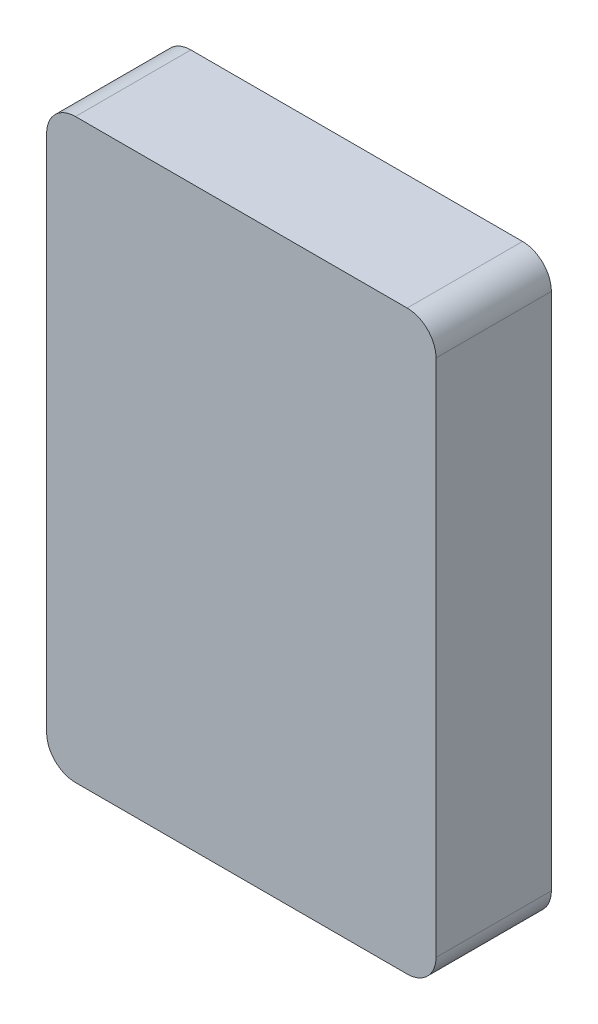
SolidWorks part; units mm, degrees
ref_plane "Front Plane" through (0, 0, 0) normal (0, 0, 1) x (1, 0, 0)
ref_plane "Top Plane" through (0, 0, 0) normal (0, 1, 0) x (1, 0, 0)
ref_plane "Right Plane" through (0, 0, 0) normal (1, 0, 0) x (0, 0, -1)
sketch "Sketch1" plane through (0, 0, 0) normal (0, 0, 1) x (1, 0, 0)
  line L1 (-13.5, 20) -> (13.5, 20)
  line L2 (-13.5, 20) -> (-13.5, -20)
  line L3 (-13.5, -20) -> (13.5, -20)
  line L4 (13.5, 20) -> (13.5, -20)
  line L5 (-13.5, 20) -> (13.5, -20) construction
  line L6 (-13.5, -20) -> (13.5, 20) construction
  point P0 (0, 0)
  dimension "D1" = 27
  dimension "D2" = 40
extrude "Boss-Extrude1" add sketch "Sketch1" along normal blind 8
fillet "Fillet1" radius 2 4 edges at (-13.5, -20, 4) (13.5, -20, 4) (13.5, 20, 4) (-13.5, 20, 4)
